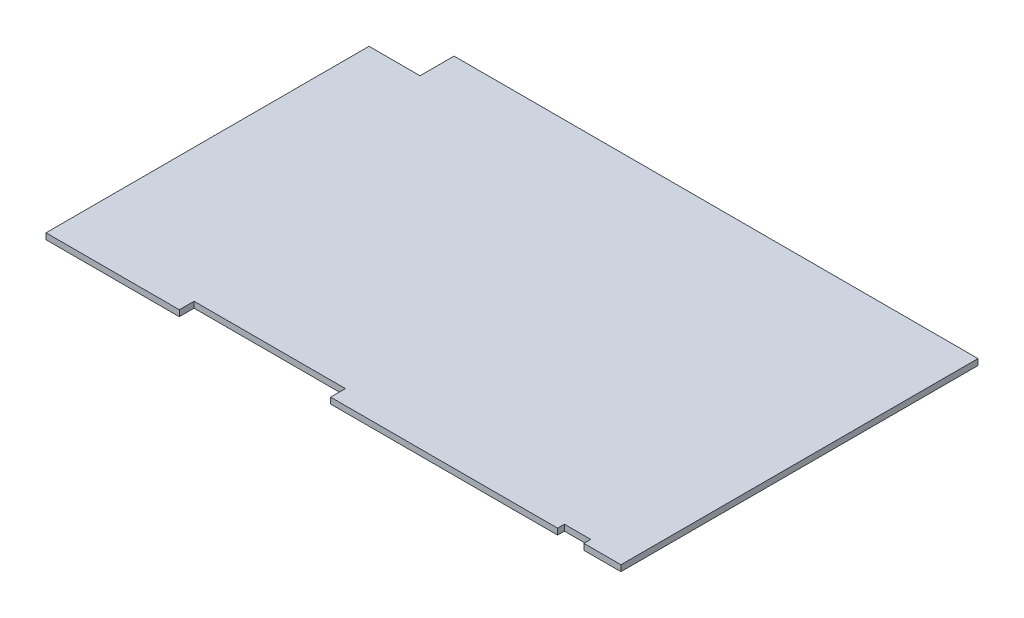
SolidWorks part; units mm, degrees
ref_plane "Front" through (0, 0, 0) normal (0, 0, 1) x (1, 0, 0)
ref_plane "Top" through (0, 0, 0) normal (0, 1, 0) x (1, 0, 0)
ref_plane "Right" through (0, 0, 0) normal (1, 0, 0) x (0, 0, -1)
sketch "Sketch1" plane through (0, 0, 0) normal (0, 1, 0) x (1, 0, 0)
  line L0 (0, 43.7585) -> (0, 0) construction
  line L1 (0, 0) -> (23.8949, 0) construction
  line L38 (-76, 38.2) -> (-76, -47.2)
  line L39 (-76, -47.2) -> (-40.75, -47.2)
  line L40 (-40.75, -47.2) -> (-40.75, -43.3)
  line L41 (-40.75, -43.3) -> (-0.75, -43.3)
  line L42 (-0.75, -43.3) -> (-0.75, -47.2)
  line L43 (-0.75, -47.2) -> (59.25, -47.2)
  line L44 (59.25, -47.2) -> (59.25, -45.39)
  line L45 (59.25, -45.39) -> (66.195, -45.39)
  line L46 (66.195, -45.39) -> (66.195, -47.2)
  line L47 (66.195, -47.2) -> (76, -47.2)
  line L48 (76, -47.2) -> (76, 47.2)
  line L49 (76, 47.2) -> (-62.5173, 47.2)
  line L50 (-62.5173, 47.2) -> (-62.5173, 38.2)
  line L51 (-62.5173, 38.2) -> (-76, 38.2)
  dimension "D1" = 94.4
  dimension "D2" = 152
  dimension "D3" = 9
  dimension "D4" = 13.4827
  dimension "D5" = 35.25
  dimension "D6" = 40
  dimension "D7" = 60
  dimension "D8" = 6.945
  dimension "D9" = 1.81
  dimension "D10" = 3.9
extrude "Boss-Extrude1" add sketch "Sketch1" along normal blind 1.6
